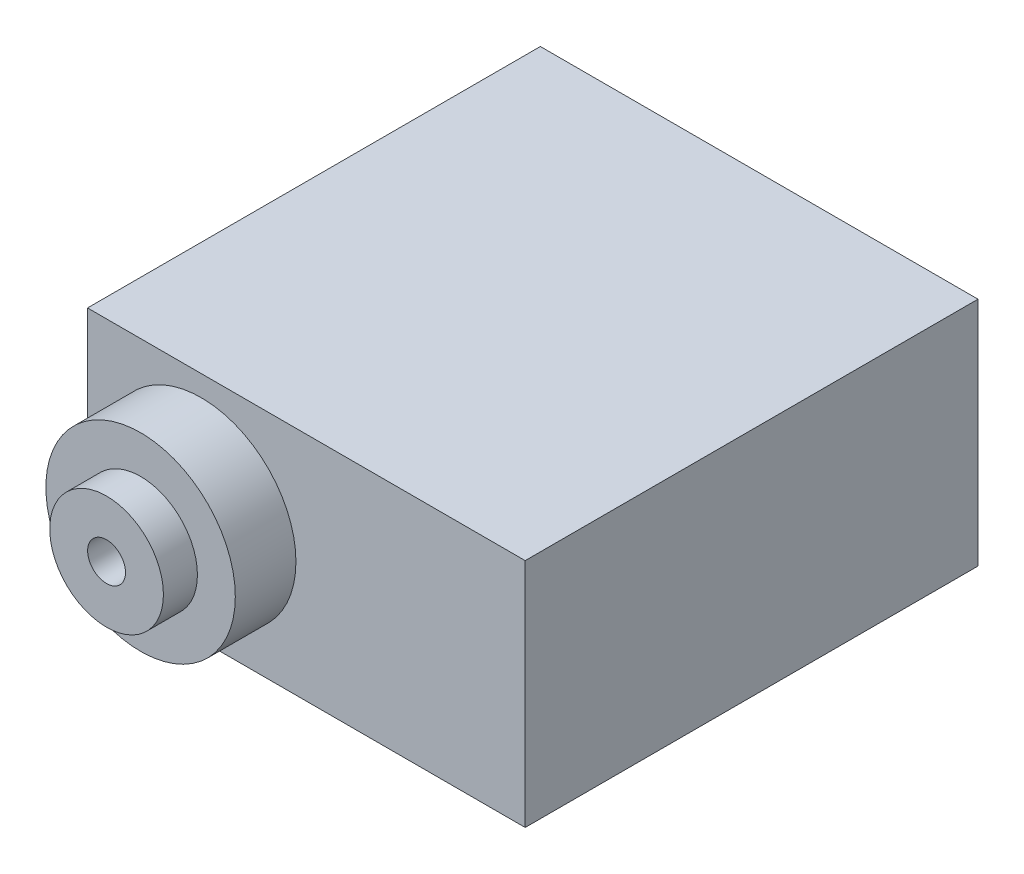
SolidWorks part; units mm, degrees
ref_plane "前视基准面" through (0, 0, 0) normal (0, 0, 1) x (1, 0, 0)
ref_plane "上视基准面" through (0, 0, 0) normal (0, 1, 0) x (1, 0, 0)
ref_plane "右视基准面" through (0, 0, 0) normal (1, 0, 0) x (0, 0, -1)
sketch "草图1" plane through (0, 0, 0) normal (0, 0, 1) x (1, 0, 0)
  line L1 (-11.8102, 3.0653) -> (11.2898, 3.0653)
  line L2 (-11.8102, 3.0653) -> (-11.8102, -9.1347)
  line L3 (-11.8102, -9.1347) -> (11.2898, -9.1347)
  line L4 (11.2898, 3.0653) -> (11.2898, -9.1347)
  dimension "D1" = 23.1
  dimension "D2" = 12.2
extrude "凸台-拉伸1" add sketch "草图1" against normal blind 27.1
sketch "草图2" plane through (0, 0, 0) normal (0, 0, 1) x (1, 0, 0)
  line L0 (-11.8102, -3.0347) -> (11.2898, -3.0347) construction
  line L1 (-11.8102, 3.0653) -> (-11.8102, -9.1347) construction
  line L2 (11.2898, -9.1347) -> (11.2898, 3.0653) construction
  circle A0 centre (-5.8102, -3.0347) radius 5
  dimension "D1" = 10
  dimension "D2" = 6
extrude "凸台-拉伸2" add sketch "草图2" along normal blind 3.2
sketch "草图3" plane through (0, 0, -27.1) normal (0, 0, -1) x (-1, 0, 0)
  line L4 (11.8102, -9.1347) -> (11.8102, 3.0653)
  line L5 (11.8102, 3.0653) -> (-11.2898, 3.0653)
  line L6 (-11.2898, 3.0653) -> (-11.2898, -9.1347)
  line L7 (-11.2898, -9.1347) -> (11.8102, -9.1347)
  line L8 (11.8102, -9.1347) -> (11.8102, 3.0653)
  line L9 (11.8102, 3.0653) -> (-11.2898, 3.0653)
  line L10 (-11.2898, 3.0653) -> (-11.2898, -9.1347)
  line L11 (-11.2898, -9.1347) -> (11.8102, -9.1347)
  dimension "D1" = 0
extrude "切除-拉伸1" cut sketch "草图3" against normal blind 3.2
sketch "草图4" plane through (0, 0, 3.2) normal (0, 0, 1) x (1, 0, 0)
  circle A0 centre (-5.8102, -3.0347) radius 3
extrude "切除-拉伸2" cut sketch "草图4" against normal blind 3.2 contours A0
sketch "草图5" plane through (0, 0, 0) normal (0, 0, 1) x (1, 0, 0)
  circle A1 centre (-5.8102, -3.0347) radius 3
  circle A2 centre (-5.8102, -3.0347) radius 3
  dimension "D1" = 0
extrude "凸台-拉伸3" add sketch "草图5" along normal blind 4.9954
sketch "草图7" plane through (0, 0, 4.9954) normal (0, 0, 1) x (1, 0, 0)
  circle A4 centre (-5.8102, -3.0347) radius 1
  circle A5 centre (-5.8102, -3.0347) radius 1
  dimension "D2" = 2
extrude "切除-拉伸3" cut sketch "草图7" against normal blind 5
